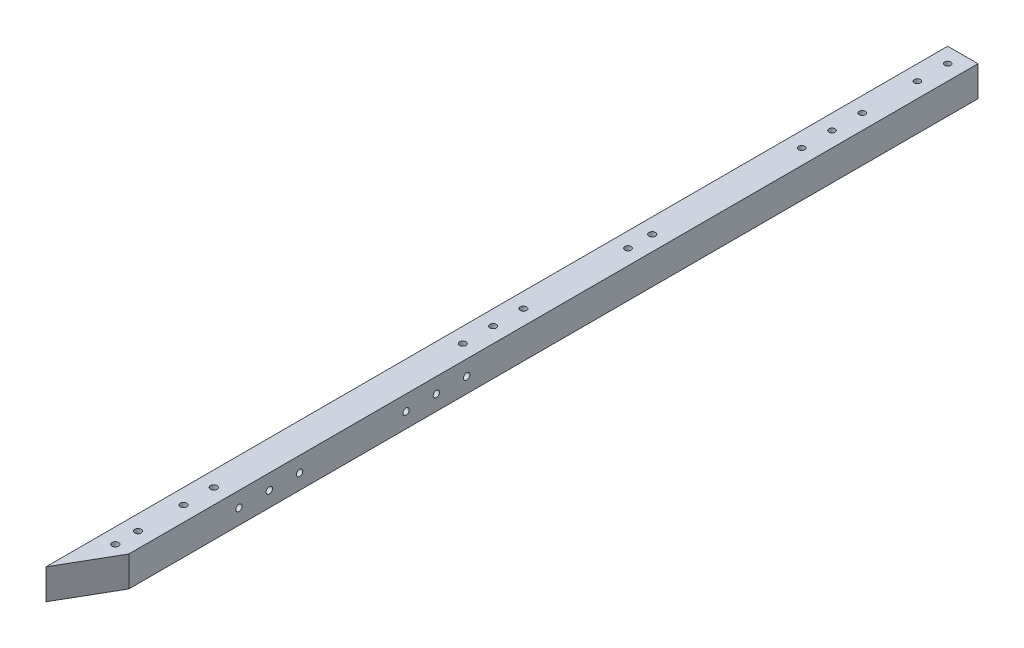
SolidWorks part; units mm, degrees
ref_plane "前视基准面" through (0, 0, 0) normal (0, 0, 1) x (1, 0, 0)
ref_plane "上视基准面" through (0, 0, 0) normal (0, 1, 0) x (1, 0, 0)
ref_plane "右视基准面" through (0, 0, 0) normal (1, 0, 0) x (0, 0, -1)
other "Configuration Table"
sketch "草图1" plane through (0, 0, 0) normal (0, 0, 1) x (1, 0, 0)
  line L1 (0, 0) -> (20, 0)
  line L2 (0, 0) -> (0, 20)
  line L3 (0, 20) -> (20, 20)
  line L4 (20, 0) -> (20, 20)
  dimension "D1" = 20
extrude "凸台-拉伸1" add sketch "草图1" along normal blind 595.07
sketch "草图2" plane through (0, 20, 0) normal (0, 1, 0) x (1, 0, 0)
  line L0 (0, -595.07) -> (20, -560.429)
  line L1 (20, -595.07) -> (20, 0) construction
  line L2 (20, -560.429) -> (20, -595.07)
  line L3 (20, -595.07) -> (0, -595.07)
  dimension "D1" = 60
extrude "切除-拉伸1" cut sketch "草图2" against normal blind 595.07
sketch "草图3" plane through (0, 20, 0) normal (0, 1, 0) x (1, 0, 0)
  line L0 (10, 0) -> (10, -236.981) construction
  line L1 (20, 0) -> (0, 0) construction
  circle A0 centre (10, -10) radius 2
  circle A1 centre (10, -30) radius 2
  circle A2 centre (10, -66.35) radius 2
  circle A3 centre (10, -86.35) radius 2
  circle A4 centre (10, -106.35) radius 2
  dimension "D3" = 4
  dimension "D1" = 10
  dimension "D2" = 20
  dimension "D4" = 66.35
  dimension "D5" = 20
  dimension "D6" = 20
extrude "切除-拉伸2" cut sketch "草图3" against normal through all both
sketch "草图4" plane through (0, 20, 0) normal (0, 1, 0) x (1, 0, 0)
  line L0 (20, -560.429) -> (0, -560.429) construction
  line L1 (0, -595.07) -> (0, 0) construction
  line L2 (10, -577.7495) -> (10, -360.9521) construction
  line L3 (20, -560.429) -> (0, -595.07) construction
  circle A0 centre (10, -544.339) radius 2.15
  circle A1 centre (10, -559.339) radius 2.15
  circle A2 centre (10, -514.339) radius 2.15
  circle A3 centre (10, -494.339) radius 2.15
  dimension "D2" = 4.3
  dimension "D3" = 4.3
  dimension "D4" = 15
  dimension "D5" = 30
  dimension "D6" = 4.3
  dimension "D7" = 20
  dimension "D8" = 4.3
  dimension "D1" = 16.09
extrude "切除-拉伸3" cut sketch "草图4" against normal up to vertex (20 mm away)
sketch "草图5" plane through (0, 20, 0) normal (0, 1, 0) x (1, 0, 0)
  line L0 (10, 0) -> (10, -609.8024) construction
  line L1 (20, 0) -> (0, 0) construction
  circle A0 centre (10, -205) radius 2.15
  circle A1 centre (10, -221) radius 2.1
  circle A2 centre (10, -310) radius 2.1
  circle A3 centre (10, -290) radius 2.1
  circle A4 centre (10, -330) radius 2.1
  dimension "D2" = 4.3
  dimension "D3" = 4.2
  dimension "D4" = 16
  dimension "D5" = 4.2
  dimension "D6" = 89
  dimension "D7" = 4.2
  dimension "D8" = 20
  dimension "D9" = 4.2
  dimension "D10" = 40
  dimension "D1" = 205
extrude "切除-拉伸4" cut sketch "草图5" against normal blind 137
sketch "草图7" plane through (20, 0, 0) normal (1, 0, 0) x (0, 0, -1)
  line L1 (-560.429, 10) -> (-425.0945, 10) construction
  line L2 (-560.429, 0) -> (-560.429, 20) construction
  circle A0 centre (-489.339, 10) radius 2.1
  circle A1 centre (-424.139, 10) radius 2.1
  dimension "D1" = 4.2
  dimension "D2" = 71.09
  dimension "D3" = 65.2
  dimension "D4" = 4.2
sketch "草图9" plane through (20, 0, 0) normal (1, 0, 0) x (0, 0, -1)
  line L0 (0, 0) -> (0, 20) construction
  line L1 (-467.6905, 43.8278) -> (-467.6905, -28.6706) construction
  line L3 (-357.4604, 30) -> (-357.4604, -17.319) construction
  circle A0 centre (-467.6905, 10) radius 2.1
  circle A1 centre (-487.6905, 10) radius 2.1
  circle A2 centre (-447.6905, 10) radius 2.1
  circle A3 centre (-357.4604, 10) radius 2.1
  circle A4 centre (-377.4604, 10) radius 2.1
  circle A5 centre (-337.4604, 10) radius 2.1
  dimension "D1" = 20
  dimension "D2" = 20
  dimension "D3" = 4.2
  dimension "D4" = 20
  dimension "D5" = 20
  dimension "D6" = 4.2
  dimension "D7" = 110.23
  dimension "D8" = 357.4604
extrude "切除-拉伸5" cut sketch "草图9" against normal blind 32
